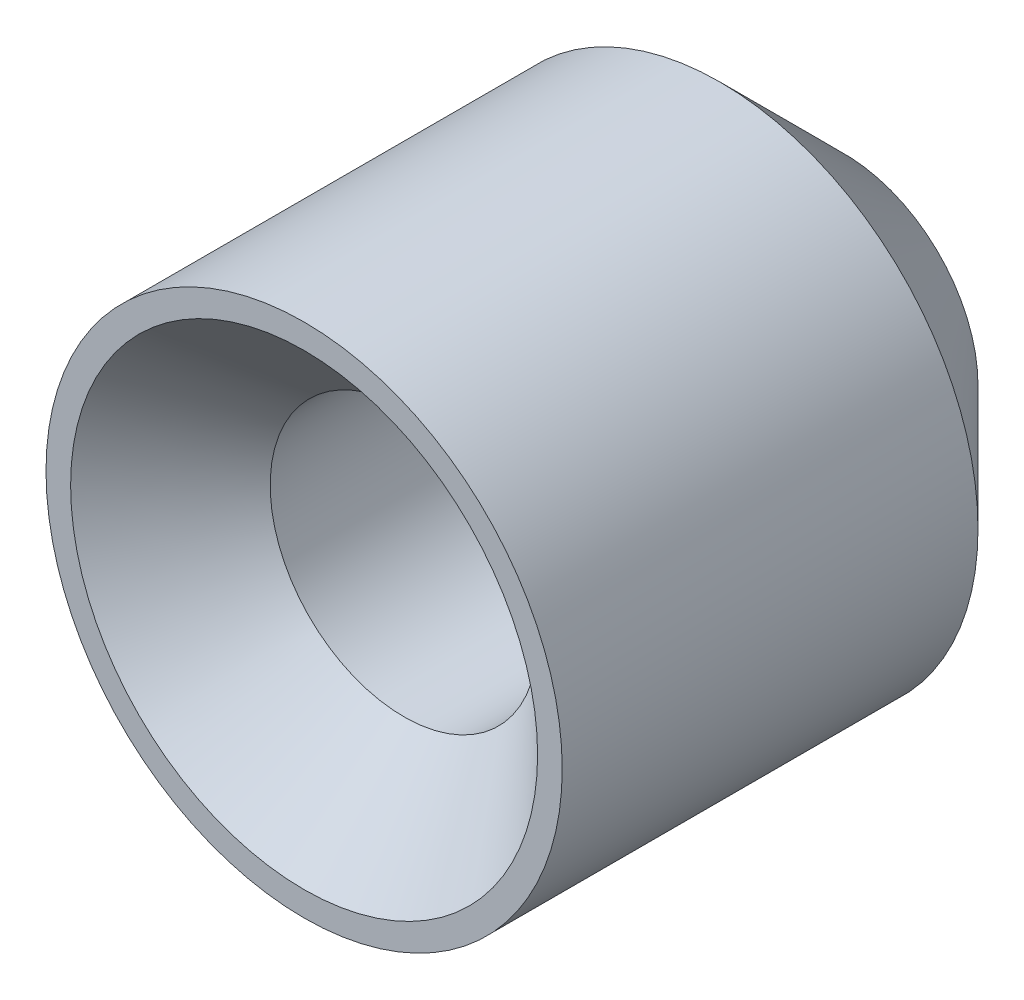
SolidWorks part; units mm, degrees
ref_plane "Front Plane" through (0, 0, 0) normal (0, 0, 1) x (1, 0, 0)
ref_plane "Top Plane" through (0, 0, 0) normal (0, 1, 0) x (1, 0, 0)
ref_plane "Right Plane" through (0, 0, 0) normal (1, 0, 0) x (0, 0, -1)
sketch "Sketch1" plane through (0, 0, 0) normal (0, 0, 1) x (1, 0, 0)
  circle A0 centre (-11.194, 3.0859) radius 4.9276
  dimension "D1" = 9.8552
extrude "Boss-Extrude1" add sketch "Sketch1" along normal blind 7.9375
sketch "Sketch4" plane through (0, 0, 0) normal (0, 0, -1) x (-1, 0, 0)
  circle A0 centre (11.194, 3.0859) radius 4.9276 construction
  circle A1 centre (11.194, 3.0859) radius 4.9276
extrude "Boss-Extrude2" add sketch "Sketch4" along normal blind 3.175 draft 45
hole_wizard "1/4-20 Tapped Hole1" positions "Sketch2" profile "Sketch3" tap size "1/4-20" standard "ANSI Inch"
sketch "Sketch2" plane through (0, 0, 7.9375) normal (0, 0, 1) x (1, 0, 0)
  point P0 (-11.194, 3.0859)
sketch "Sketch3" plane through (-11.194, 3.0859, 7.9375) normal (1, 0, 0) x (0, -1, 0)
  line L0 (0, 0) -> (0, 18.0438)
  line L1 (0, 18.0438) -> (2.5527, 16.51)
  line L2 (2.5527, 16.51) -> (2.5527, 1.905)
  line L3 (2.5527, 1.905) -> (4.4577, 0)
  line L5 (4.4577, 0) -> (0, 0)
  line L6 (-2.5527, 1.905) -> (-4.4577, 0) construction
  line L10 (0, 18.0438) -> (-2.5527, 16.51) construction
  line L11 (0, -6.35) -> (0, 107.95) construction
  dimension "Tap Drill Dia." = 5.1054
  dimension "Tap Drill Depth" = 16.51
  dimension "Near C'Sink Dia." = 8.9154
  dimension "Near C'Sink Angle" = 90
  dimension "Drill Angle" = 118
cosmetic thread "Hole Thread1"
